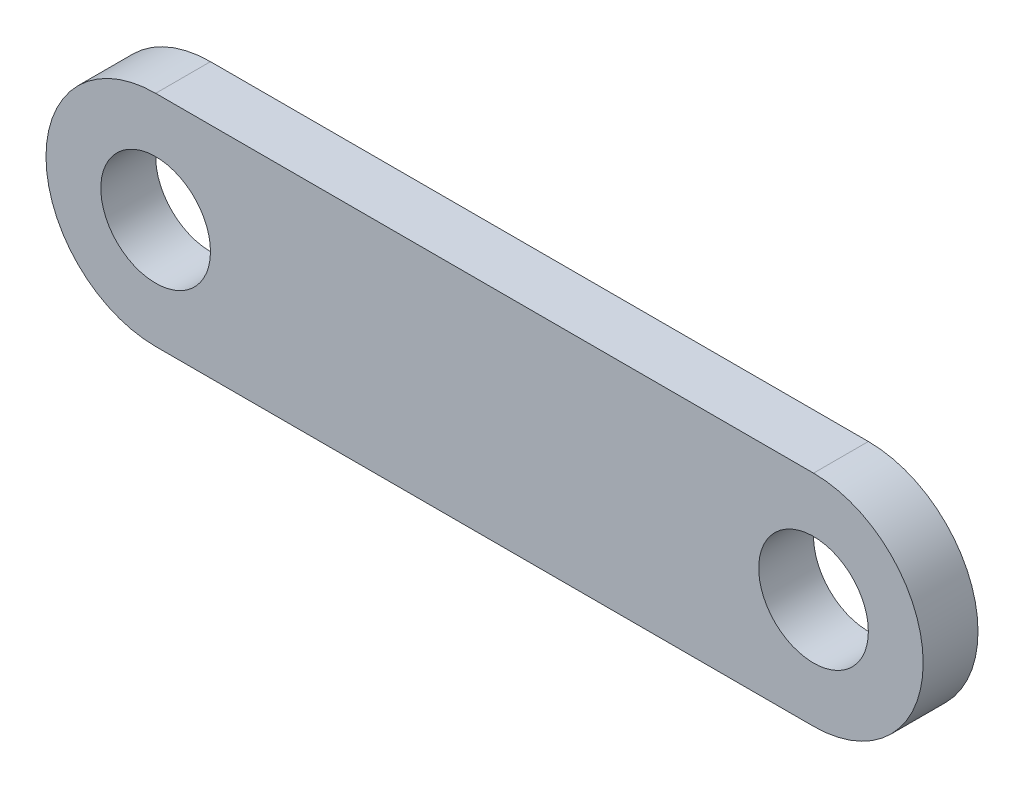
SolidWorks part; units mm, degrees
ref_plane "前视基准面" through (0, 0, 0) normal (0, 0, 1) x (1, 0, 0)
ref_plane "上视基准面" through (0, 0, 0) normal (0, 1, 0) x (1, 0, 0)
ref_plane "右视基准面" through (0, 0, 0) normal (1, 0, 0) x (0, 0, -1)
other "Configuration Table"
sketch "草图1" plane through (0, 0, 0) normal (0, 0, 1) x (1, 0, 0)
  line L0 (-47.2078, 10.8729) -> (72.7922, 10.8729) construction
  line L1 (-47.2078, 30.8729) -> (72.7922, 30.8729)
  line L2 (-47.2078, -9.1271) -> (72.7922, -9.1271)
  arc A0 (-47.2078, 30.8729) -> (-47.2078, -9.1271) centre (-47.2078, 10.8729) ccw
  arc A1 (72.7922, -9.1271) -> (72.7922, 30.8729) centre (72.7922, 10.8729) ccw
  circle A2 centre (72.7922, 10.8729) radius 10
  circle A3 centre (-47.2078, 10.8729) radius 10
  point P2 (12.7922, 10.8729)
  dimension "D2" = 20
  dimension "D1" = 120
extrude "凸台-拉伸1" add sketch "草图1" along normal blind 10
